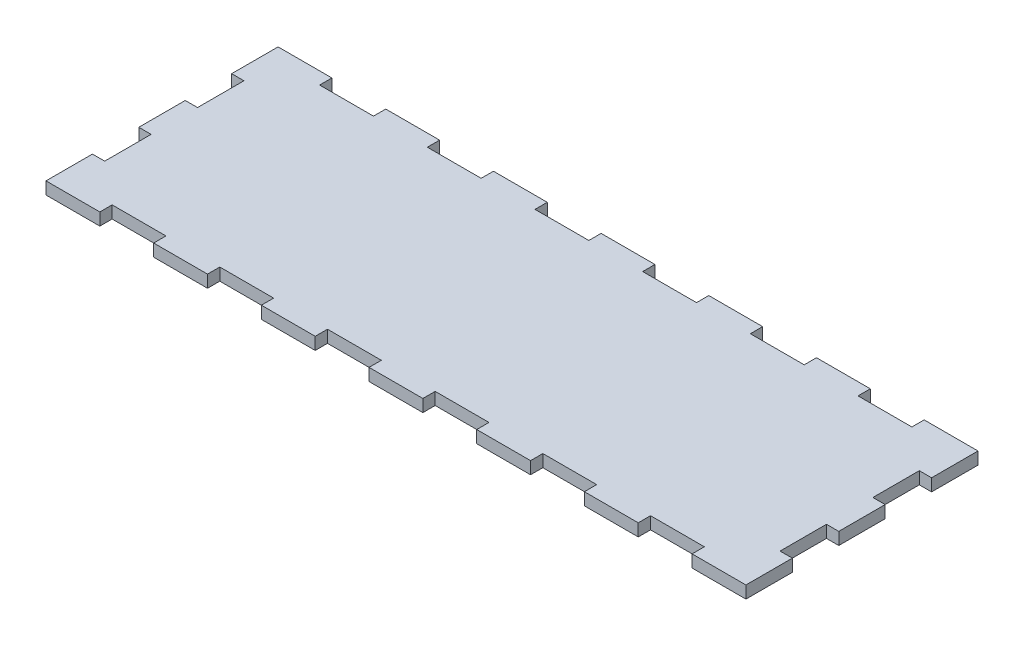
SolidWorks part; units mm, degrees
ref_plane "Front Plane" through (0, 0, 0) normal (0, 0, 1) x (1, 0, 0)
ref_plane "Top Plane" through (0, 0, 0) normal (0, 1, 0) x (1, 0, 0)
ref_plane "Right Plane" through (0, 0, 0) normal (1, 0, 0) x (0, 0, -1)
sketch "Sketch1" plane through (0, 0, 0) normal (0, 1, 0) x (1, 0, 0)
  line L1 (-69.469, 24.003) -> (75.311, 24.003)
  line L2 (-69.469, 24.003) -> (-69.469, -24.003)
  line L3 (-69.469, -24.003) -> (75.311, -24.003)
  line L4 (75.311, 24.003) -> (75.311, -24.003)
  point P0 (0, 0)
  point P6 (0, 0)
  point P7 (0, 0)
  point P11 (0, 0)
  point P12 (22.479, 0)
  dimension "D1" = 48.006
  dimension "D2" = 144.78
extrude "Boss-Extrude1" add sketch "Sketch1" along normal blind 2.54
sketch "Sketch2" plane through (0, 2.54, 0) normal (0, 1, 0) x (1, 0, 0)
  line L0 (-69.469, 24.003) -> (-69.469, 14.4018)
  line L1 (75.311, 24.003) -> (64.1741, 24.003)
  line L2 (-69.469, 24.003) -> (-69.469, -24.003) construction
  line L3 (-69.469, 24.003) -> (75.311, 24.003) construction
  line L4 (-69.469, 14.4018) -> (-66.929, 14.4018)
  line L5 (-66.929, 14.4018) -> (-66.929, 4.8006)
  line L6 (-66.929, 4.8006) -> (-69.469, 4.8006)
  line L7 (-69.469, 4.8006) -> (-69.469, -4.8006)
  line L8 (-69.469, -4.8006) -> (-66.929, -4.8006)
  line L9 (-66.929, -4.8006) -> (-66.929, -14.4018)
  line L10 (-66.929, -14.4018) -> (-69.469, -14.4018)
  line L11 (-69.469, -14.4018) -> (-69.469, -24.003)
  line L12 (75.311, 24.003) -> (75.311, -24.003) construction
  line L13 (64.1741, 24.003) -> (64.1741, 21.463)
  line L14 (64.1741, 21.463) -> (53.0372, 21.463)
  line L15 (53.0372, 21.463) -> (53.0372, 24.003)
  line L16 (53.0372, 24.003) -> (41.9002, 24.003)
  line L17 (41.9002, 24.003) -> (41.9002, 21.463)
  line L18 (41.9002, 21.463) -> (30.7633, 21.463)
  line L19 (30.7633, 21.463) -> (30.7633, 24.003)
  line L20 (30.7633, 24.003) -> (19.6264, 24.003)
  line L21 (19.6264, 24.003) -> (19.6264, 21.463)
  line L22 (19.6264, 21.463) -> (8.4895, 21.463)
  line L23 (8.4895, 21.463) -> (8.4895, 24.003)
  line L24 (8.4895, 24.003) -> (-2.6475, 24.003)
  line L25 (-2.6475, 24.003) -> (-2.6475, 21.463)
  line L26 (-2.6475, 21.463) -> (-13.7844, 21.463)
  line L27 (-13.7844, 21.463) -> (-13.7844, 24.003)
  line L28 (-13.7844, 24.003) -> (-24.9213, 24.003)
  line L29 (-24.9213, 24.003) -> (-24.9213, 21.463)
  line L30 (-24.9213, 21.463) -> (-36.0582, 21.463)
  line L31 (-36.0582, 21.463) -> (-36.0582, 24.003)
  line L32 (-36.0582, 24.003) -> (-47.1952, 24.003)
  line L33 (-47.1952, 24.003) -> (-47.1952, 21.463)
  line L34 (-47.1952, 21.463) -> (-58.3321, 21.463)
  line L35 (-58.3321, 21.463) -> (-58.3321, 24.003)
  line L36 (-58.3321, 24.003) -> (-69.469, 24.003)
  line L37 (75.311, -24.003) -> (64.1741, -24.003)
  line L38 (64.1741, -24.003) -> (64.1741, -21.463)
  line L39 (64.1741, -21.463) -> (53.0372, -21.463)
  line L40 (53.0372, -21.463) -> (53.0372, -24.003)
  line L41 (53.0372, -24.003) -> (41.9002, -24.003)
  line L42 (41.9002, -24.003) -> (41.9002, -21.463)
  line L43 (41.9002, -21.463) -> (30.7633, -21.463)
  line L44 (30.7633, -21.463) -> (30.7633, -24.003)
  line L45 (30.7633, -24.003) -> (19.6264, -24.003)
  line L46 (19.6264, -24.003) -> (19.6264, -21.463)
  line L47 (19.6264, -21.463) -> (8.4895, -21.463)
  line L48 (8.4895, -21.463) -> (8.4895, -24.003)
  line L49 (8.4895, -24.003) -> (-2.6475, -24.003)
  line L50 (-2.6475, -24.003) -> (-2.6475, -21.463)
  line L51 (-2.6475, -21.463) -> (-13.7844, -21.463)
  line L52 (-13.7844, -21.463) -> (-13.7844, -24.003)
  line L53 (-13.7844, -24.003) -> (-24.9213, -24.003)
  line L54 (-24.9213, -24.003) -> (-24.9213, -21.463)
  line L55 (-24.9213, -21.463) -> (-36.0582, -21.463)
  line L56 (-36.0582, -21.463) -> (-36.0582, -24.003)
  line L57 (-36.0582, -24.003) -> (-47.1952, -24.003)
  line L58 (-47.1952, -24.003) -> (-47.1952, -21.463)
  line L59 (-47.1952, -21.463) -> (-58.3321, -21.463)
  line L60 (-58.3321, -21.463) -> (-58.3321, -24.003)
  line L61 (-58.3321, -24.003) -> (-69.469, -24.003)
  line L63 (-69.469, -24.003) -> (75.311, -24.003) construction
  line L64 (75.311, 24.003) -> (75.311, 14.4018)
  line L65 (75.311, 14.4018) -> (72.771, 14.4018)
  line L66 (72.771, 14.4018) -> (72.771, 4.8006)
  line L67 (72.771, 4.8006) -> (75.311, 4.8006)
  line L68 (75.311, 4.8006) -> (75.311, -4.8006)
  line L69 (75.311, -4.8006) -> (72.771, -4.8006)
  line L70 (72.771, -4.8006) -> (72.771, -14.4018)
  line L71 (72.771, -14.4018) -> (75.311, -14.4018)
  line L72 (75.311, -14.4018) -> (75.311, -24.003)
  dimension "D1" = 2.54
extrude "Cut-Extrude1" cut sketch "Sketch2" against normal blind 2.54 flip side to cut
